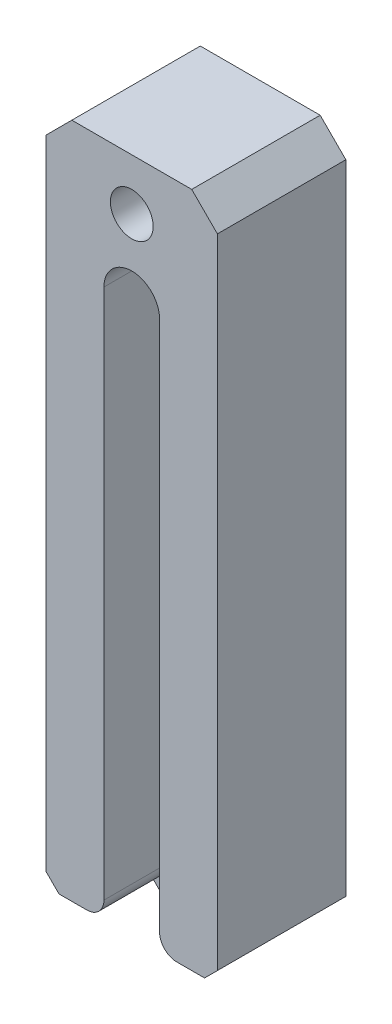
SolidWorks part; units mm, degrees
ref_plane "Plan de face" through (0, 0, 0) normal (0, 0, 1) x (1, 0, 0)
ref_plane "Plan de dessus" through (0, 0, 0) normal (0, 1, 0) x (1, 0, 0)
ref_plane "Plan de droite" through (0, 0, 0) normal (1, 0, 0) x (0, 0, -1)
sketch "Esquisse1" plane through (0, 0, 0) normal (0, 0, 1) x (1, 0, 0)
  line L1 (0, 0) -> (20, 0)
  line L2 (0, 0) -> (0, 85)
  line L3 (0, 85) -> (20, 85)
  line L4 (20, 0) -> (20, 85)
  dimension "D1" = 20
  dimension "D2" = 85
extrude "Boss.-Extru.1" add sketch "Esquisse1" along normal blind 15
sketch "Esquisse2" plane through (0, 0, 15) normal (0, 0, 1) x (1, 0, 0)
  line L0 (10, 0) -> (10, 85) construction
  line L1 (0, 0) -> (20, 0) construction
  line L2 (20, 85) -> (0, 85) construction
  line L3 (10, 12) -> (10, 70) construction
  line L4 (6.75, 12) -> (6.75, 70)
  line L5 (13.25, 12) -> (13.25, 70)
  arc A0 (6.75, 12) -> (13.25, 12) centre (10, 12) ccw
  arc A1 (13.25, 70) -> (6.75, 70) centre (10, 70) ccw
  circle A2 centre (10, 79) radius 2.5
  point P8 (10, 41)
  dimension "D4" = 5
  dimension "D1" = 6.5
  dimension "D2" = 58
  dimension "D3" = 12
  dimension "D5" = 6
extrude "Enlèv. mat.-Extru.1" cut sketch "Esquisse2" against normal up to vertex (15 mm away) up to point (20, 85, 0)
sketch "Esquisse3" plane through (0, 0, 15) normal (0, 0, 1) x (1, 0, 0)
  line L0 (0, 6) -> (20, 6)
  line L1 (0, 85) -> (0, 0) construction
  line L2 (20, 0) -> (20, 85) construction
  line L3 (20, 6) -> (20, 0)
  line L4 (20, 0) -> (0, 0)
  line L5 (0, 0) -> (0, 6)
  dimension "D1" = 6
extrude "Enlèv. mat.-Extru.2" cut sketch "Esquisse3" against normal blind 9
sketch "Esquisse6" plane through (0, 0, 15) normal (0, 0, 1) x (1, 0, 0)
  line L0 (7.5, 0) -> (0, 7.5)
  line L1 (0, 0) -> (20, 0) construction
  line L2 (0, 85) -> (0, 6) construction
  line L3 (0, 7.5) -> (0, -7.5)
  line L4 (0, -7.5) -> (20, -7.5)
  line L5 (20, -7.5) -> (20, 7.5)
  line L6 (20, 7.5) -> (12.5, 0)
  line L7 (12.5, 0) -> (7.5, 0)
  line L8 (10, 8.75) -> (10, 0) construction
  line L9 (20, 6) -> (20, 85) construction
  arc A0 (6.75, 12) -> (13.25, 12) centre (10, 12) ccw construction
  dimension "D1" = 5
  dimension "D2" = 15
extrude "Enlèv. mat.-Extru.3" cut sketch "Esquisse6" against normal up to vertex (15 mm away) up to point (20, 0, 0)
sketch "Esquisse7" plane through (0, 0, 15) normal (0, 0, 1) x (1, 0, 0)
  line L0 (6.75, 70) -> (6.75, 12) construction
  line L1 (6.75, 14) -> (13.25, 14)
  line L2 (6.75, 14) -> (6.75, 6)
  line L3 (6.75, 6) -> (13.25, 6)
  line L4 (13.25, 14) -> (13.25, 6)
  line L5 (18.5, 6) -> (1.5, 6) construction
  line L6 (13.25, 12) -> (13.25, 70) construction
  dimension "D1" = 8
extrude "Enlèv. mat.-Extru.4" cut sketch "Esquisse7" against normal up to vertex (9 mm away) up to point (12.5, 0, 6)
fillet "Congé1" radius 2 2 edges at (13.25, 6, 10.5) (6.75, 6, 10.5)
chamfer "Chanfrein1" distance 3 angle 45 2 edges at (20, 85, 7.5) (0, 85, 7.5)
